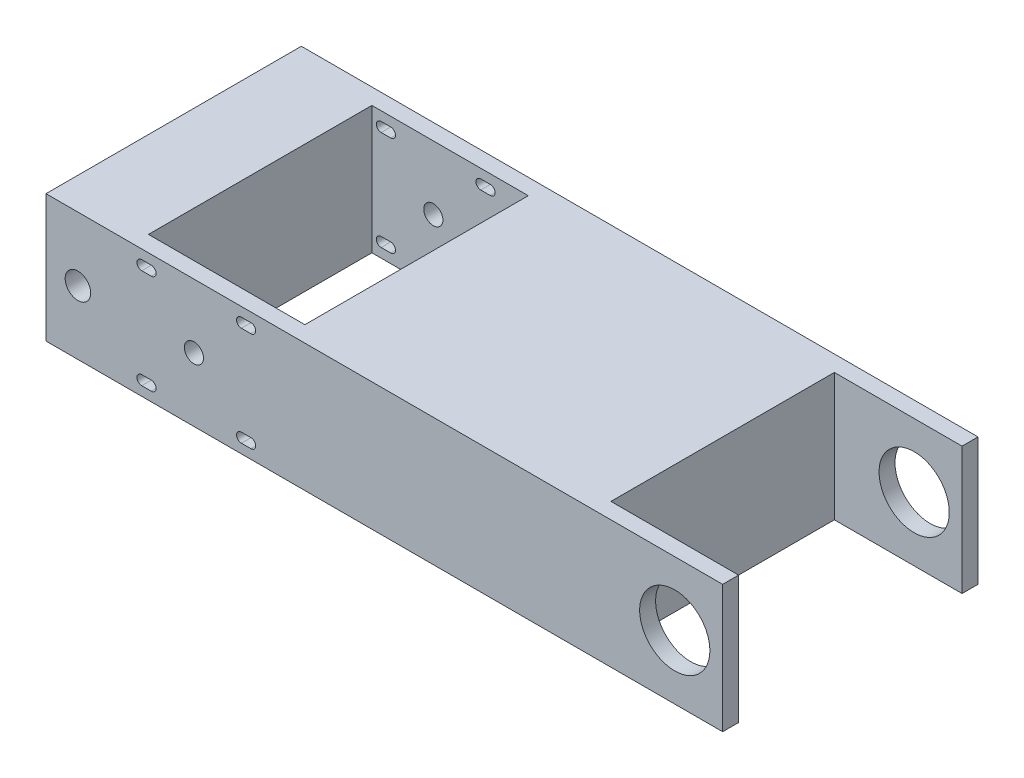
SolidWorks part; units mm, degrees
ref_plane "Front Plane" through (0, 0, 0) normal (0, 0, 1) x (1, 0, 0)
ref_plane "Top Plane" through (0, 0, 0) normal (0, 1, 0) x (1, 0, 0)
ref_plane "Right Plane" through (0, 0, 0) normal (1, 0, 0) x (0, 0, -1)
sketch "Sketch1" plane through (0, 0, 0) normal (0, 0, 1) x (1, 0, 0)
  line L0 (-106, -20) -> (-106, 20)
  line L1 (-106, 20) -> (106, 20)
  line L3 (-106, -20) -> (106, -20)
  line L4 (106, 20) -> (106, -20)
  line L5 (-106, 20) -> (106, -20) construction
  line L6 (-106, -20) -> (106, 20) construction
  line L7 (-76, 15.6) -> (-76, -15.6) construction
  line L8 (-76, 15.6) -> (-43.3, 15.6)
  line L9 (-76, 15.6) -> (-73, 15.6) construction
  line L10 (-76, 17.1) -> (-73, 17.1)
  line L11 (-76, 14.1) -> (-73, 14.1)
  line L12 (-44.8, 15.6) -> (-41.8, 15.6) construction
  line L13 (-44.8, 17.1) -> (-41.8, 17.1)
  line L14 (-44.8, 14.1) -> (-41.8, 14.1)
  line L15 (-76, -15.6) -> (-73, -15.6) construction
  line L16 (-76, -14.1) -> (-73, -14.1)
  line L17 (-76, -17.1) -> (-73, -17.1)
  line L18 (-44.8, -15.6) -> (-41.8, -15.6) construction
  line L19 (-44.8, -14.1) -> (-41.8, -14.1)
  line L20 (-44.8, -17.1) -> (-41.8, -17.1)
  circle A0 centre (-96, 0) radius 4
  circle A1 centre (-76, 15.6) radius 1.5 construction
  circle A2 centre (-44.8, 15.6) radius 1.5 construction
  circle A3 centre (-76, -15.6) radius 1.5 construction
  circle A4 centre (-44.8, -15.6) radius 1.5 construction
  circle A5 centre (-59.65, 0) radius 3
  circle A6 centre (91, 0) radius 11
  arc A7 (-76, 17.1) -> (-76, 14.1) centre (-76, 15.6) ccw
  arc A8 (-73, 14.1) -> (-73, 17.1) centre (-73, 15.6) ccw
  arc A9 (-44.8, 17.1) -> (-44.8, 14.1) centre (-44.8, 15.6) ccw
  arc A10 (-41.8, 14.1) -> (-41.8, 17.1) centre (-41.8, 15.6) ccw
  arc A11 (-76, -14.1) -> (-76, -17.1) centre (-76, -15.6) ccw
  arc A12 (-73, -17.1) -> (-73, -14.1) centre (-73, -15.6) ccw
  arc A13 (-44.8, -14.1) -> (-44.8, -17.1) centre (-44.8, -15.6) ccw
  arc A14 (-41.8, -17.1) -> (-41.8, -14.1) centre (-41.8, -15.6) ccw
  point P0 (0, 0)
  point P16 (-76, 0)
  point P22 (-74.5, 15.6)
  point P28 (-43.3, 15.6)
  point P34 (-74.5, -15.6)
  point P40 (-43.3, -15.6)
  point P46 (-59.65, 15.6)
  dimension "D3" = 8
  dimension "D5" = 31.2
  dimension "D1" = 3
  dimension "D7" = 31.2
  dimension "D9" = 6
  dimension "D10" = 22
  dimension "D4" = 10
  dimension "D2" = 212
  dimension "D6" = 40
  dimension "D8" = 20
  dimension "D11" = 15
  dimension "D12" = 1.5
extrude "Boss-Extrude1" add sketch "Sketch1" along normal mid plane 80
sketch "Sketch2" plane through (0, 0, 0) normal (0, 1, 0) x (1, 0, 0)
  line L0 (-106, 40) -> (106, 40) construction
  line L1 (-78.9, 35) -> (-29.9, 35)
  line L2 (-78.9, 35) -> (-78.9, -35)
  line L3 (-78.9, -35) -> (-29.9, -35)
  line L4 (-29.9, 35) -> (-29.9, -35)
  line L5 (-78.9, 35) -> (-29.9, -35) construction
  line L6 (-78.9, -35) -> (-29.9, 35) construction
  line L8 (106, -40) -> (106, 40) construction
  line L9 (66, 35) -> (106, 35)
  line L10 (66, 35) -> (66, -35)
  line L11 (66, -35) -> (106, -35)
  line L12 (106, 35) -> (106, -35)
  line L13 (66, 35) -> (106, -35) construction
  line L14 (66, -35) -> (106, 35) construction
  point P0 (-54.4, 0)
  point P11 (86, 0)
  dimension "D1" = 49
  dimension "D2" = 5
  dimension "D3" = 54.4
  dimension "D4" = 40
extrude "Cut-Extrude3" cut sketch "Sketch2" against normal through all both and the other way through all
